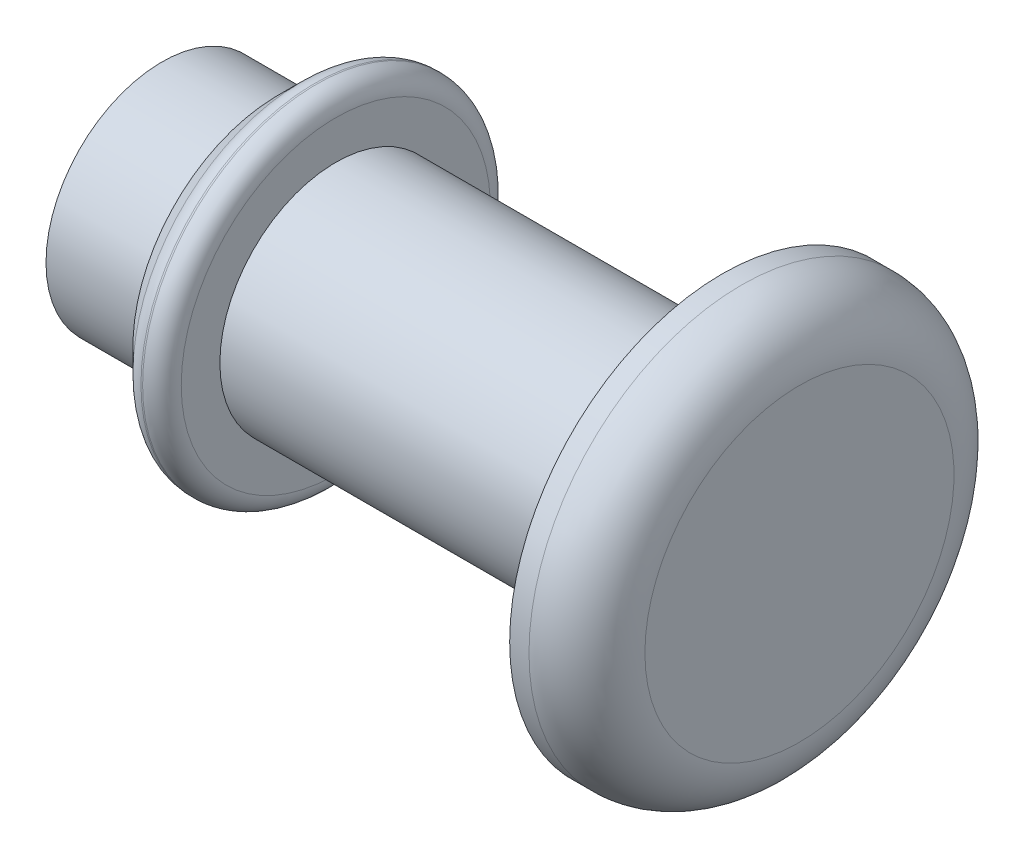
SolidWorks part; units mm, degrees
ref_plane "Front Plane" through (0, 0, 0) normal (0, 0, 1) x (1, 0, 0)
ref_plane "Top Plane" through (0, 0, 0) normal (0, 1, 0) x (1, 0, 0)
ref_plane "Right Plane" through (0, 0, 0) normal (1, 0, 0) x (0, 0, -1)
sketch "Sketch2" plane through (0, 0, 0) normal (0, 0, 1) x (1, 0, 0)
  line L0 (-42.3, 0) -> (42.3, 0) construction
  line L1 (0, 0) -> (0, 5.5)
  line L2 (0, 5.5) -> (-2, 5.5)
  line L3 (-2, 5.5) -> (-2, 3)
  line L4 (-2, 3) -> (-12, 3)
  line L5 (-12, 3) -> (-12, 4.5)
  line L6 (-12, 4.5) -> (-13.5, 4.5)
  line L7 (-13.5, 4.5) -> (-13.5, 3)
  line L8 (-13.5, 3) -> (-16.5, 3)
  line L9 (-16.5, 3) -> (-16.5, 0)
  line L10 (-12, 4.5) -> (-12, 0) construction
  line L11 (-2, 5.5) -> (-2, 0) construction
  line L12 (0, 0) -> (-16.5, 0)
  point P4 (0, 0)
  dimension "D1" = 4.5
  dimension "D2" = 5.5
  dimension "D3" = 3
  dimension "D4" = 10
  dimension "D5" = 2
  dimension "D6" = 3
  dimension "D7" = 1.5
  dimension "D8" = 3
revolve "Revolve1" add sketch "Sketch2" angle 360 about L0
fillet "Fillet1" radius 1.5 1 edges at (0, 0, 5.5)
chamfer "Chamfer1" distance 0.75 angle 45 1 edges at (-13.5, 0, 4.5)
fillet "Fillet2" radius 0.5 2 edges at (-12.75, 0, -4.5) (-12, 0, 4.5)
equation "\"Wall Length\"= 10mm"
equation "\"Rivet Head Height\"= 2mm"
equation "\"Rive Head Radiust\"= 5.5mm"
equation "\"Crushed Radius\"= 4.5mm"
equation "\"Radius Shaft\"= 3mm"
equation "\"D1@Sketch2\"=\"Crushed Radius\""
equation "\"D2@Sketch2\"=\"Rive Head Radiust\""
equation "\"D3@Sketch2\"=\"Radius Shaft\""
equation "\"D4@Sketch2\"=\"Wall Length\""
equation "\"Crushed Tail Length\"= 3mm"
equation "\"D5@Sketch2\"=\"Rivet Head Height\""
equation "\"D6@Sketch2\"=\"Crushed Tail Length\""
equation "\"D7@Sketch2\"=\"Crushed Tail Height\""
equation "\"Crushed Tail Height\"= 1.5mm"
equation "\"Crushed Head Fillet\"= 0.5mm"
equation "\"Crushed Head Chamfer\"= .75mm"
equation "\"D1@Fillet1\"=\"Rivet Head Fillet\""
equation "\"D1@Chamfer1\"=\"Crushed Head Chamfer\""
equation "\"D1@Fillet2\"=\"Crushed Head Fillet\""
equation "\"Rivet Head Fillet\"= 1.5mm"
equation "\"Rivet Shank\"= 3mm"
equation "\"D8@Sketch2\"=\"Rivet Shank\""
